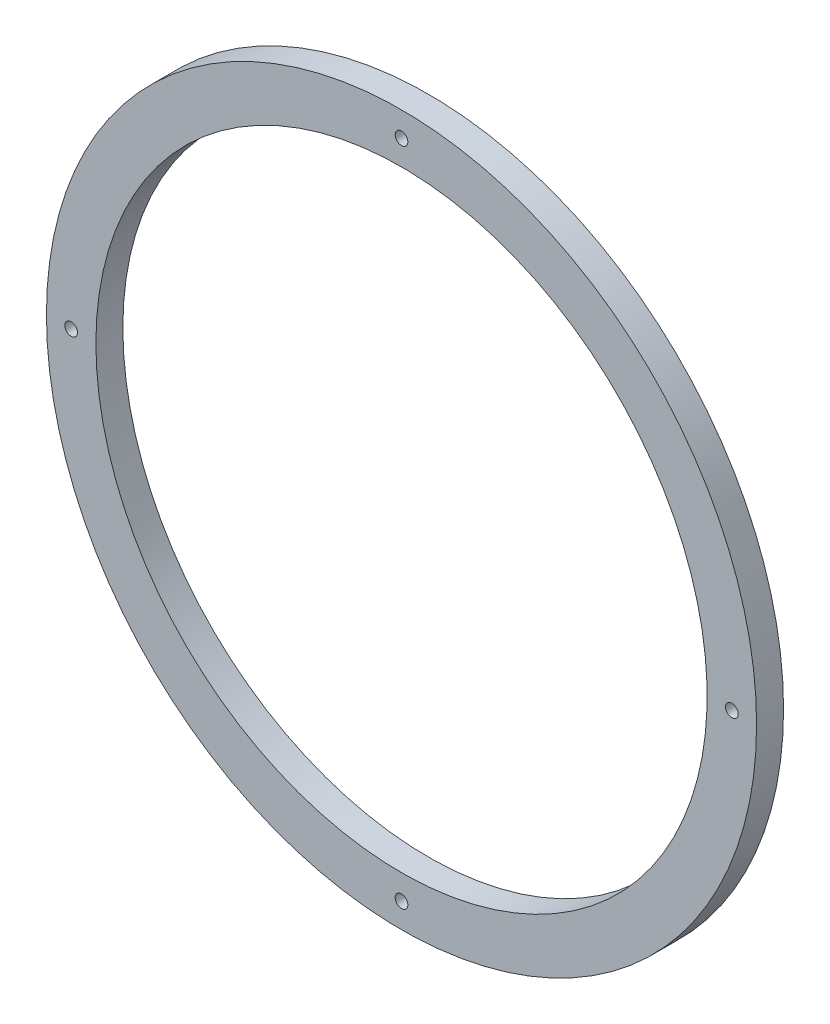
SolidWorks part; units mm, degrees
material "6061 Alloy"
ref_plane "Front Plane" through (0, 0, 0) normal (0, 0, 1) x (1, 0, 0)
ref_plane "Top Plane" through (0, 0, 0) normal (0, 1, 0) x (1, 0, 0)
ref_plane "Right Plane" through (0, 0, 0) normal (1, 0, 0) x (0, 0, -1)
sketch "Sketch1" plane through (0, 0, 0) normal (0, 0, 1) x (1, 0, 0)
  line L0 (0, 93.345) -> (0, 0) construction
  line L1 (0, 0) -> (-93.345, 0) construction
  circle A0 centre (0, 0) radius 100.33
  circle A1 centre (0, 0) radius 86.36
  circle A2 centre (0, 93.345) radius 1.7859
  circle A3 centre (93.345, 0) radius 1.7859
  circle A4 centre (0, -93.345) radius 1.7859
  circle A5 centre (-93.345, 0) radius 1.7859
  point P16 (0, 0)
  dimension "D1" = 200.66
  dimension "D4" = 3.5719
  dimension "D3" = 93.345
  dimension "D6" = 93.345
  dimension "D2" = 13.97
  dimension "D5" = 4
extrude "Boss-Extrude1" add sketch "Sketch1" along normal blind 7.62
